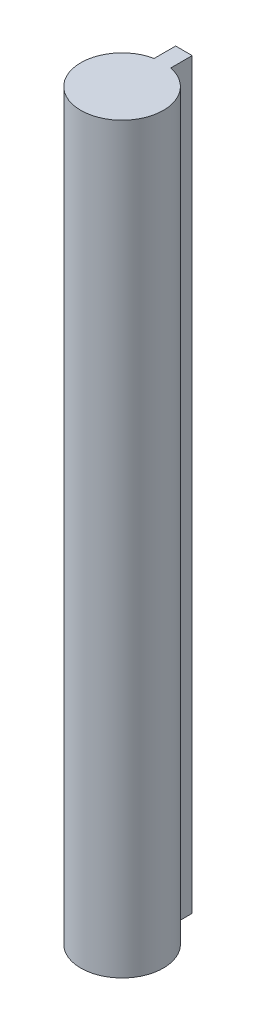
SolidWorks part; units mm, degrees
ref_plane "Front Plane" through (0, 0, 0) normal (0, 0, 1) x (1, 0, 0)
ref_plane "Top Plane" through (0, 0, 0) normal (0, 1, 0) x (1, 0, 0)
ref_plane "Right Plane" through (0, 0, 0) normal (1, 0, 0) x (0, 0, -1)
sketch "Sketch1" plane through (0, 0, 0) normal (0, 1, 0) x (1, 0, 0)
  line L0 (0, 2) -> (0, 2.8)
  line L1 (0, 2.8) -> (0.5, 2.8)
  line L2 (0, 2.8) -> (-0.5, 2.8)
  line L3 (-0.5, 2.8) -> (-0.5, 1.9365)
  line L4 (-0.5, 1.9365) -> (0.5, 2.8)
  line L5 (0.5, 1.9365) -> (0.5, 2.8)
  circle A0 centre (0, 0) radius 2
extrude "Boss-Extrude1" add sketch "Sketch1" along normal blind 45 contours L3 L4 L0 L2 | L0 L4 L1 | A0 L5 L4 L0 | A0 L0 L4 | A0
sketch "Sketch2" plane through (0, 45, 0) normal (0, 1, 0) x (1, 0, 0)
  line L0 (0, 1) -> (0, 1.5)
  line L1 (0, 1.5) -> (0.2, 1.5)
  line L2 (0.2, 1.5) -> (0.2, 0.9798)
  line L3 (0.2, 0.9798) -> (0, 1.5)
  line L4 (-0.2015, 1.5) -> (0, 1.5)
  line L5 (-0.2015, 1.5) -> (-0.2015, 0.9795)
  circle A0 centre (0, 0) radius 1
  circle A1 centre (0, 0) radius 4.1818
  line M3 (-0.5, 2.8) -> (-0.5, 1.9365)
  arc M4 (-0.5, 1.9365) -> (0.5, 1.9365) centre (0, 0) ccw
  line M5 (0.5, 1.9365) -> (0.5, 2.8)
  line M6 (0.5, 2.8) -> (-0.5, 2.8)
extrude "Cut-Extrude1" cut sketch "Sketch2" against normal blind 53 contours A1 M3 M6 M5 M4 | A0 L5 L4 L1 L2 M6 M3 M4 M5
sketch "Sketch3" plane through (0, 45, 0) normal (0, 1, 0) x (1, 0, 0)
  circle A0 centre (0, 0) radius 2.3283
extrude "Cut-Extrude2" cut sketch "Sketch3" against normal blind 27
